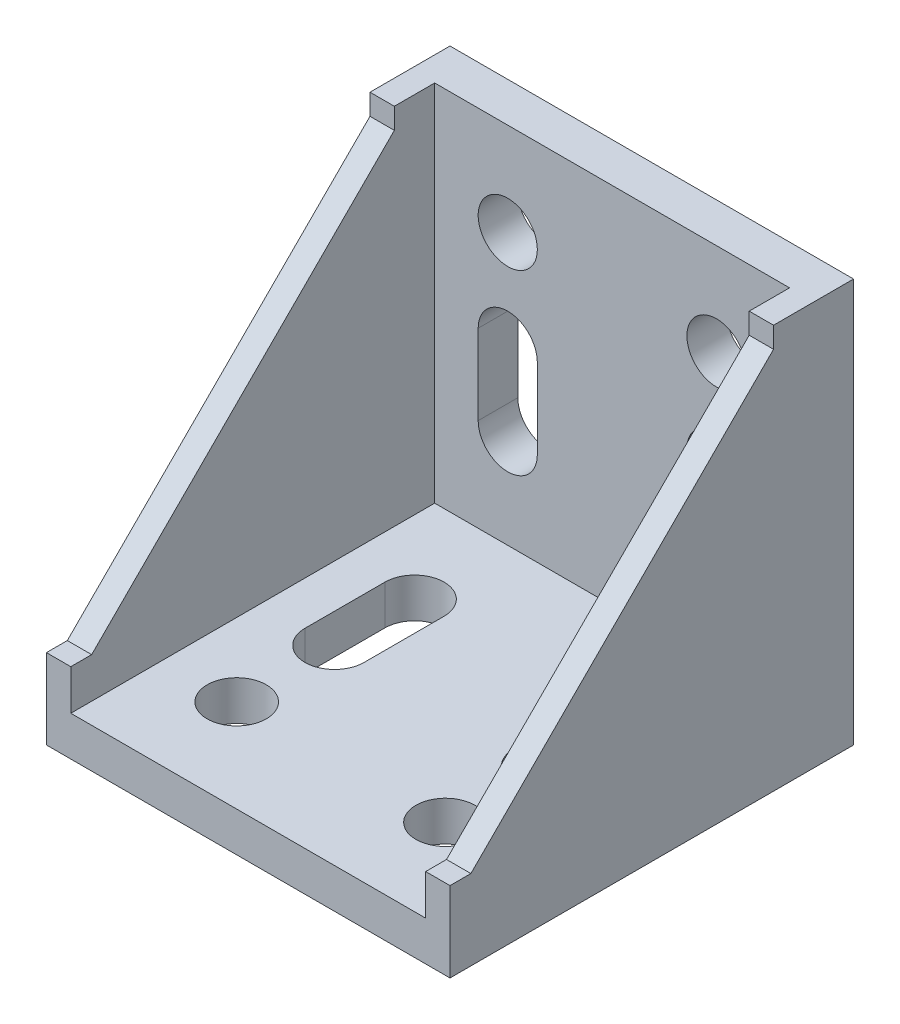
SolidWorks part; units mm, degrees
ref_plane "前视基准面" through (0, 0, 0) normal (0, 0, 1) x (1, 0, 0)
ref_plane "上视基准面" through (0, 0, 0) normal (0, 1, 0) x (1, 0, 0)
ref_plane "右视基准面" through (0, 0, 0) normal (1, 0, 0) x (0, 0, -1)
sketch "草图1" plane through (0, 0, 0) normal (0, 0, 1) x (1, 0, 0)
  line L1 (-29, 29) -> (29, 29)
  line L2 (-29, 29) -> (-29, -29)
  line L3 (-29, -29) -> (29, -29)
  line L4 (29, 29) -> (29, -29)
  line L5 (-29, 29) -> (29, -29) construction
  line L6 (-29, -29) -> (29, 29) construction
  point P0 (0, 0)
  dimension "D1" = 58
  dimension "D2" = 58
extrude "凸台-拉伸1" add sketch "草图1" along normal blind 5.7
sketch "草图2" plane through (0, 0, 0) normal (0, 0, -1) x (-1, 0, 0)
  line L0 (29, 29) -> (29, -29) construction
  line L1 (-29, -29) -> (29, -29)
  line L2 (-29, -29) -> (-29, -23.3)
  line L3 (-29, -23.3) -> (29, -23.3)
  line L4 (29, -29) -> (29, -23.3)
  dimension "D1" = 5.7
extrude "凸台-拉伸2" add sketch "草图2" against normal blind 58
sketch "草图3" plane through (-29, 0, 0) normal (-1, 0, 0) x (0, 0, 1)
  line L0 (5.7, 29) -> (11.5, 29)
  line L1 (11.5, 29) -> (11.5, 26)
  line L2 (11.5, 26) -> (55, -17.5)
  line L3 (55, -17.5) -> (58, -17.5)
  line L4 (58, -17.5) -> (58, -23.3)
  line L5 (58, -23.3) -> (5.7, -23.3)
  line L6 (5.7, -23.3) -> (5.7, 29)
  dimension "D1" = 5.8
  dimension "D2" = 3
  dimension "D3" = 3
  dimension "D4" = 5.8
extrude "凸台-拉伸3" add sketch "草图3" against normal blind 3.5
sketch "草图4" plane through (0, 0, 5.7) normal (0, 0, 1) x (1, 0, 0)
  line L0 (-15, -9.9009) -> (-15, 1.5991) construction
  line L1 (-19.25, -9.9009) -> (-19.25, 1.5991)
  line L2 (-10.75, -9.9009) -> (-10.75, 1.5991)
  line L3 (0, 0) -> (0, 19.2156) construction
  circle A0 centre (-15, 15.652) radius 4.25
  arc A1 (-19.25, -9.9009) -> (-10.75, -9.9009) centre (-15, -9.9009) ccw
  arc A2 (-10.75, 1.5991) -> (-19.25, 1.5991) centre (-15, 1.5991) ccw
  point P4 (-15, -4.1509)
  dimension "D1" = 8.5
  dimension "D2" = 4.25
  dimension "D3" = 11.5
  dimension "D4" = 15
extrude "切除-拉伸1" cut sketch "草图4" against normal through all
mirror "镜向1" about plane through (0, 0, 0) normal (1, 0, 0) of "切除-拉伸1", "凸台-拉伸3"
ref_plane "基准面1" through (0, -14.5, 14.5) normal (0, -0.7071, 0.7071) x (1, 0, 0)
mirror "镜向2" about plane through (0, -14.5, 14.5) normal (0, -0.7071, 0.7071) of "镜向1", "切除-拉伸1"
